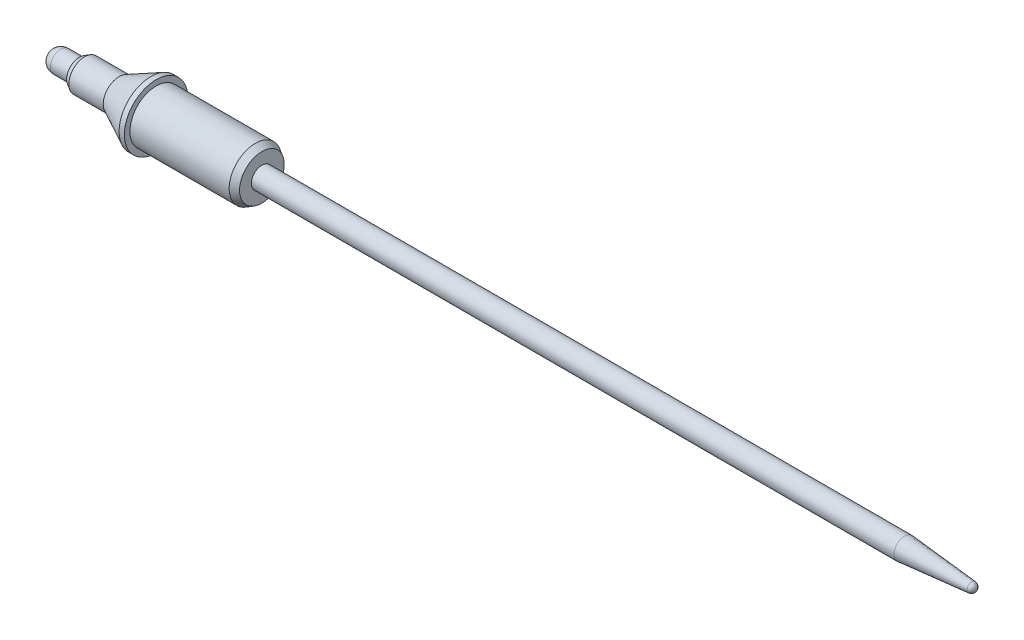
SolidWorks part; units mm, degrees
ref_plane "Frontal" through (0, 0, 0) normal (0, 0, 1) x (1, 0, 0)
ref_plane "Superior" through (0, 0, 0) normal (0, 1, 0) x (1, 0, 0)
ref_plane "Lateral" through (0, 0, 0) normal (1, 0, 0) x (0, 0, -1)
sketch "Esboço1" plane through (0, 0, 0) normal (0, 0, 1) x (1, 0, 0)
  line L0 (0, 0.4) -> (0.7, 0.4)
  line L1 (0.7, 0.4845) -> (0.9, 0.6)
  line L2 (0.7, 0.4845) -> (0.7, 0.4)
  line L3 (0.9, 0.6) -> (2.2, 0.6)
  line L4 (-0.4, 0) -> (34.8126, 0) construction
  line L5 (2.2, 0.6) -> (3.4, 1.2)
  line L6 (3.4, 1.2) -> (3.6, 1.2)
  line L7 (3.6, 1.2) -> (3.6, 0.99)
  line L8 (3.6, 0.99) -> (7.35, 0.99)
  line L9 (7.35, 0.99) -> (7.6, 0.8457)
  line L10 (7.6, 0.8457) -> (7.6, 0.4)
  line L11 (7.6, 0.4) -> (31.8956, 0.4)
  line L12 (31.8956, 0.4) -> (34.4372, 0.1776)
  line L13 (-0.4, 0) -> (34.6, 0)
  line L14 (0.7, 0.4) -> (7.6, 0.4) construction
  arc A0 (0, 0.4) -> (-0.4, 0) centre (0, 0) ccw
  arc A1 (34.6, 0) -> (34.4372, 0.1776) centre (34.4217, 0) ccw
  dimension "D17" = 0.1783
  dimension "D1" = 1.2
  dimension "D2" = 30
  dimension "D3" = 0.2
  dimension "D4" = 1.1
  dimension "D5" = 2.4
  dimension "D6" = 1.98
  dimension "D7" = 0.8
  dimension "D8" = 0.25
  dimension "D9" = 30
  dimension "D10" = 4
  dimension "D11" = 1.5
  dimension "D12" = 1.4
  dimension "D13" = 0.2
  dimension "D14" = 0.8
  dimension "D15" = 35
  dimension "D16" = 5
  dimension "D18" = 27
revolve "Revolução1" add sketch "Esboço1" angle 360 about L4
